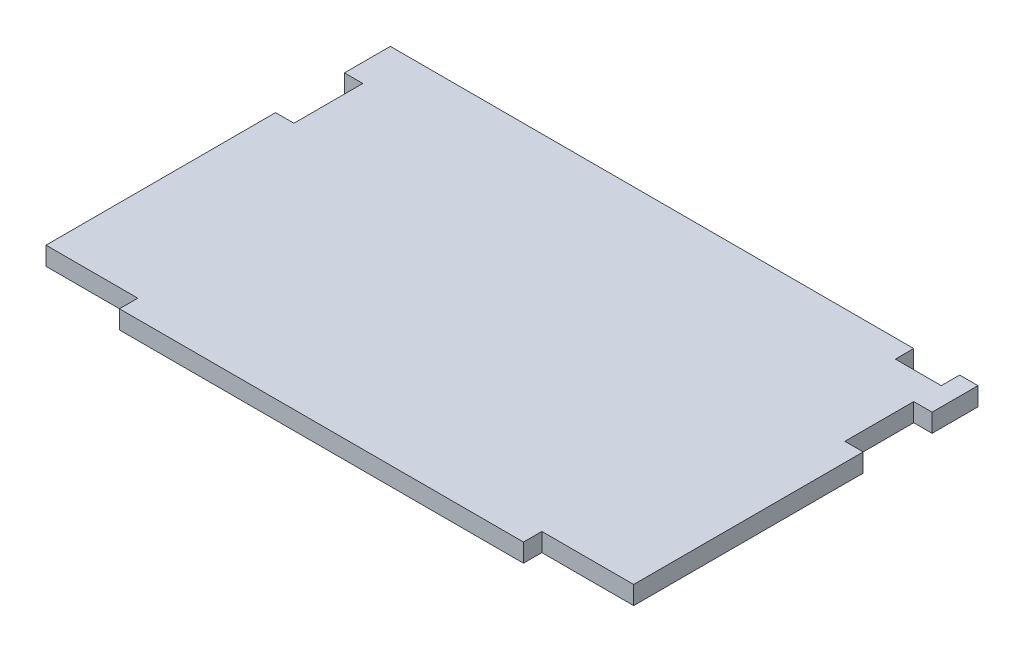
SolidWorks part; units mm, degrees
ref_plane "Front Plane" through (0, 0, 0) normal (0, 0, 1) x (1, 0, 0)
ref_plane "Top Plane" through (0, 0, 0) normal (0, 1, 0) x (1, 0, 0)
ref_plane "Right Plane" through (0, 0, 0) normal (1, 0, 0) x (0, 0, -1)
sketch "Sketch1" plane through (0, 0, 0) normal (0, 1, 0) x (1, 0, 0)
  line L0 (0, 65) -> (4, 65)
  line L1 (0, 0) -> (20, 0)
  line L2 (0, 0) -> (0, 50)
  line L3 (0, 75) -> (114, 75)
  line L4 (128, 0) -> (128, 50)
  line L5 (4, 65) -> (4, 50)
  line L6 (4, 50) -> (0, 50)
  line L7 (0, 65) -> (0, 75)
  line L8 (128, 65) -> (124, 65)
  line L9 (124, 65) -> (124, 50)
  line L10 (124, 50) -> (128, 50)
  line L11 (128, 65) -> (128, 75)
  line L12 (108, 0) -> (128, 0)
  line L13 (124, 75) -> (128, 75)
  line L14 (108, 0) -> (108, -4)
  line L15 (108, -4) -> (20, -4)
  line L16 (20, 0) -> (20, -4)
  line L18 (114, 75) -> (114, 71)
  line L19 (114, 71) -> (124, 71)
  line L20 (124, 75) -> (124, 71)
  dimension "D1" = 128
  dimension "D2" = 75
  dimension "D3" = 15
  dimension "D4" = 10
  dimension "D5" = 4
  dimension "D6" = 4
  dimension "D7" = 4
  dimension "D8" = 20
  dimension "D9" = 20
  dimension "D11" = 10
  dimension "D12" = 4
  dimension "D10" = 4
extrude "Boss-Extrude1" add sketch "Sketch1" along normal blind 4
equation "\"D6@Sketch1\"=\"D5@Sketch1\""
